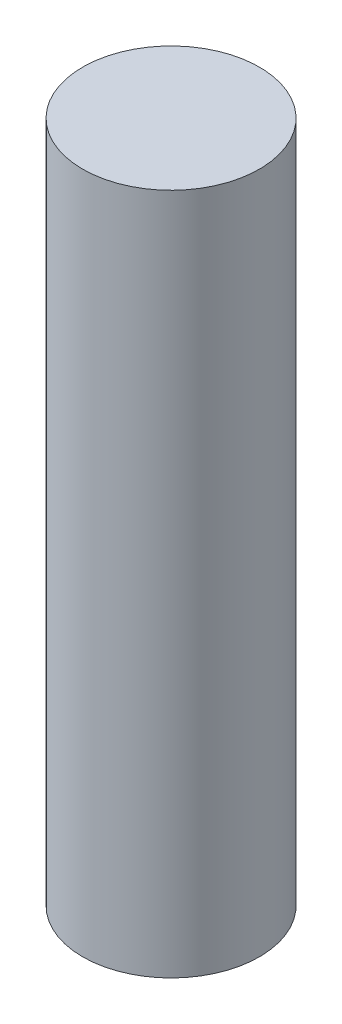
SolidWorks part; units mm, degrees
ref_plane "Front Plane" through (0, 0, 0) normal (0, 0, 1) x (1, 0, 0)
ref_plane "Top Plane" through (0, 0, 0) normal (0, 1, 0) x (1, 0, 0)
ref_plane "Right Plane" through (0, 0, 0) normal (1, 0, 0) x (0, 0, -1)
sketch "Sketch1" plane through (0, 0, 0) normal (0, 1, 0) x (1, 0, 0)
  circle A0 centre (0, 0) radius 3.175
  dimension "D1" = 6.35
extrude "Boss-Extrude1" add sketch "Sketch1" along normal blind 24.5
